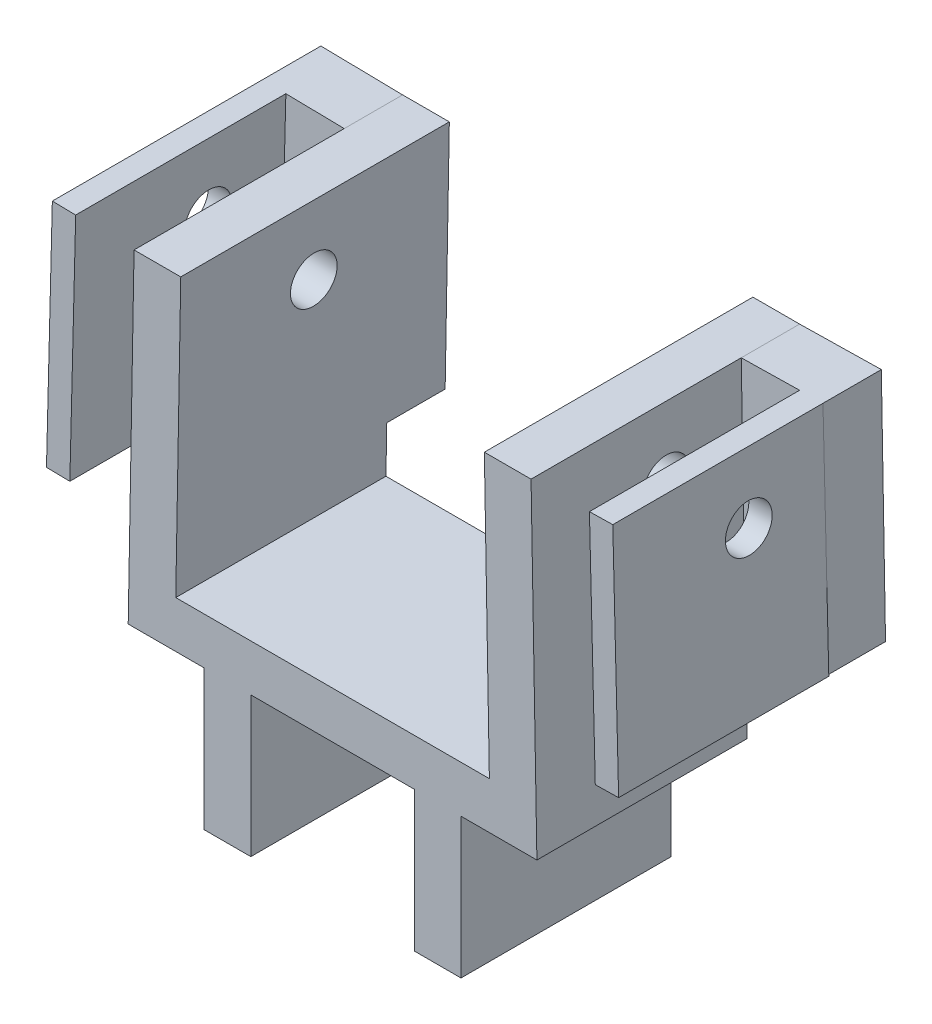
SolidWorks part; units mm, degrees
ref_plane "Front Plane" through (0, 0, 0) normal (0, 0, 1) x (1, 0, 0)
ref_plane "Top Plane" through (0, 0, 0) normal (0, 1, 0) x (1, 0, 0)
ref_plane "Right Plane" through (0, 0, 0) normal (1, 0, 0) x (0, 0, -1)
sketch "Sketch1" plane through (0, 0, 0) normal (0, 0, 1) x (1, 0, 0)
  line L0 (-8.6894, 3.4133) -> (-8.5, 14)
  line L1 (-8.7505, 0) -> (-5.5, 0)
  line L2 (-8.7505, 0) -> (-8.6894, 3.4133)
  line L3 (-6.7147, 2) -> (6.7147, 2)
  line L4 (8.7505, 0) -> (8.6958, 3.0559)
  line L6 (-5.5, 0) -> (-5.5, -6)
  line L7 (-5.5, -6) -> (-3.5, -6)
  line L8 (-3.5, 0) -> (-3.5, -6)
  line L10 (3.5, 0) -> (3.5, -6)
  line L11 (3.5, -6) -> (5.5, -6)
  line L12 (5.5, 0) -> (5.5, -6)
  line L13 (-8.5, 14) -> (-6.5, 14)
  line L14 (-6.5, 14) -> (-6.7147, 2)
  line L15 (-3.5, 0) -> (3.5, 0)
  line L17 (8.6958, 3.0559) -> (8.5, 14)
  line L18 (8.5, 14) -> (6.5, 14)
  line L19 (6.5, 14) -> (6.7147, 2)
  line L20 (5.5, 0) -> (8.7505, 0)
  line L21 (0, 2) -> (0, 0) construction
  dimension "D1" = 7
  dimension "D2" = 6
  dimension "D3" = 2
  dimension "D4" = 88.975
  dimension "D5" = 14
  dimension "D6" = 2
  dimension "D7" = 2
  dimension "D8" = 17
  dimension "D9" = 88.975
extrude "Boss-Extrude1" add sketch "Sketch1" along normal blind 9
sketch "Sketch3" plane through (0, 0, 0) normal (0, 0, -1) x (-1, 0, 0)
  line L0 (-8.5, 14) -> (-6.5, 14)
  line L1 (-8.5, 14) -> (-8.6789, 4)
  line L2 (-6.5, 14) -> (-6.6789, 4)
  line L3 (-8.6789, 4) -> (-6.6789, 4)
  line L5 (6.5, 14) -> (8.5, 14)
  line L6 (6.5, 14) -> (6.6789, 4)
  line L7 (8.5, 14) -> (8.6789, 4)
  line L8 (6.6789, 4) -> (8.6789, 4)
  line L9 (-8.7505, 0) -> (-8.5, 14) construction
  line L10 (8.5, 14) -> (8.7505, 0) construction
  line L11 (8.7505, 0) -> (5.5, 0) construction
  line L12 (-5.5, 0) -> (-8.7505, 0) construction
  point P0 (-6.7175, 1.8439)
  point P16 (-6.7505, 0)
  point P17 (8.6807, 3.9018)
  point P22 (0, 0)
  dimension "D1" = 4
  dimension "D2" = 4
extrude "Boss-Extrude2" add sketch "Sketch3" along normal blind 2.5
sketch "Sketch5" plane through (8.7477, 0.1565, 0) normal (0.9998, 0.0179, 0) x (0, 0, -1)
  line L1 (2.5, 13.8457) -> (0, 13.8457)
  line L2 (2.5, 13.8457) -> (2.5, 3.8457)
  line L3 (2.5, 3.8457) -> (0, 3.8457)
  line L4 (0, 13.8457) -> (0, 3.8457)
  dimension "D1" = 2.5
  dimension "D2" = 10
extrude "Boss-Extrude3" add sketch "Sketch5" along normal blind 3.5
sketch "Sketch6" plane through (0, 0, 0) normal (0, 0, 1) x (1, 0, 0)
  line L0 (10.9994, 14.0447) -> (11.9994, 14.0626)
  line L1 (10.9994, 14.0447) -> (11.2499, 4.0447)
  line L2 (11.9994, 14.0626) -> (12.2499, 4.0626)
  line L3 (11.2499, 4.0447) -> (12.2499, 4.0626)
  line L4 (11.9994, 14.0626) -> (8.5, 14) construction
  dimension "D1" = 1
  dimension "D2" = 10
extrude "Boss-Extrude4" add sketch "Sketch6" along normal blind 9
mirror "Mirror2" about plane through (0, 0, 0) normal (1, 0, 0) of "Boss-Extrude3", "Boss-Extrude4"
sketch "Sketch7" plane through (-6.7483, 0.1207, 0) normal (0.9998, -0.0179, 0) x (0, 0, -1)
  line L0 (-3.25, 13.8815) -> (-3.25, 1.8796) construction
  line L1 (-9, 13.8815) -> (2.5, 13.8815) construction
  line L2 (-9, 1.8796) -> (0, 1.8796) construction
  circle A0 centre (-3.25, 10.8796) radius 1
  point P10 (-3.25, 8.9108)
  dimension "D1" = 2
  dimension "D2" = 9
extrude "Cut-Extrude2" cut sketch "Sketch7" against normal blind 9
mirror "Mirror3" about plane through (0, 0, 0) normal (1, 0, 0) of "Cut-Extrude2"
